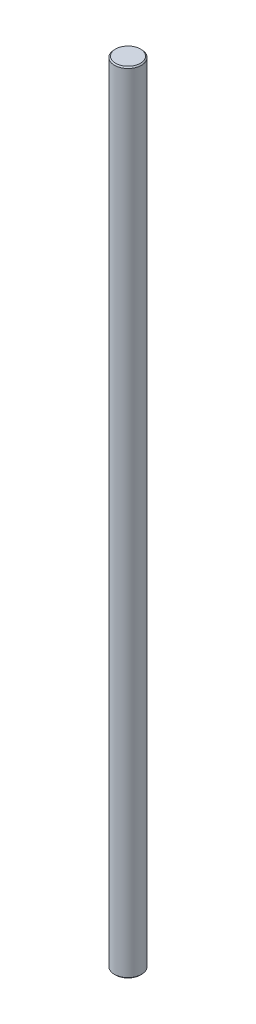
SolidWorks part; units mm, degrees
ref_plane "Front Plane" through (0, 0, 0) normal (0, 0, 1) x (1, 0, 0)
ref_plane "Top Plane" through (0, 0, 0) normal (0, 1, 0) x (1, 0, 0)
ref_plane "Right Plane" through (0, 0, 0) normal (1, 0, 0) x (0, 0, -1)
sketch "Sketch1" plane through (0, 0, 0) normal (0, 1, 0) x (1, 0, 0)
  circle A0 centre (0, 0) radius 6
  dimension "D1" = 12
extrude "Boss-Extrude1" add sketch "Sketch1" along normal mid plane 350
chamfer "Chamfer1" distance 0.5 angle 45 2 edges at (0, -175, 6) (0, 175, 6)
